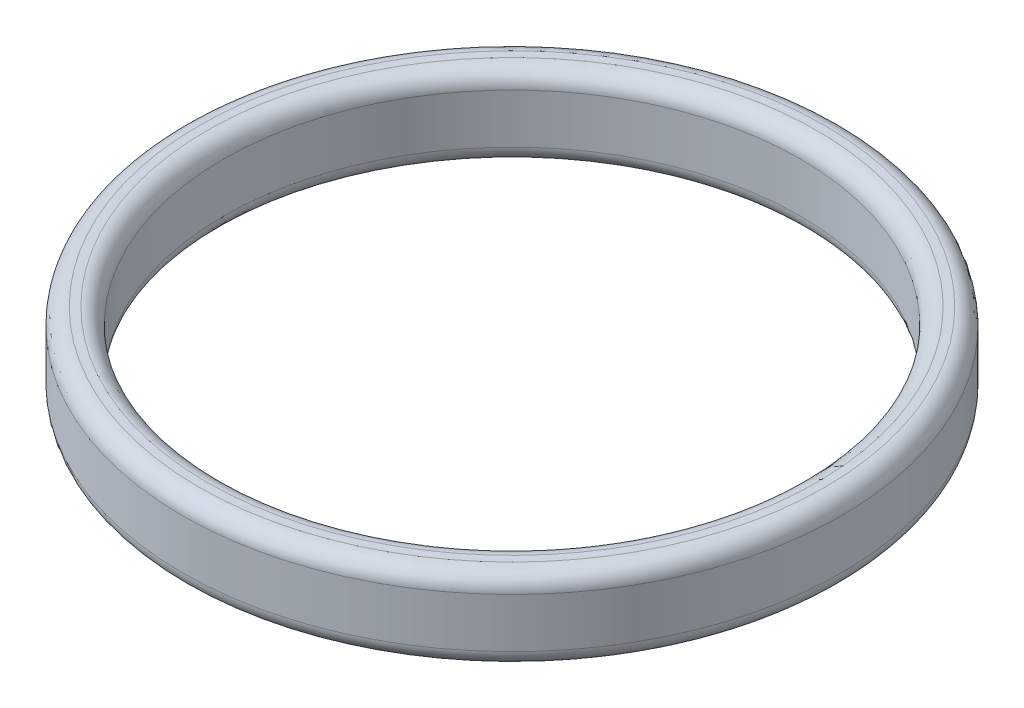
SolidWorks part; units mm, degrees
material "Plain Carbon Steel"
ref_plane "Front Plane" through (0, 0, 0) normal (0, 0, 1) x (1, 0, 0)
ref_plane "Top Plane" through (0, 0, 0) normal (0, 1, 0) x (1, 0, 0)
ref_plane "Right Plane" through (0, 0, 0) normal (1, 0, 0) x (0, 0, -1)
sketch "Sketch1" plane through (0, 0, 0) normal (0, 1, 0) x (1, 0, 0)
  circle A0 centre (0, 0) radius 4
  circle A1 centre (0, 0) radius 3.5
  dimension "D1" = 8
  dimension "D2" = 7
extrude "Boss-Extrude1" add sketch "Sketch1" along normal blind 1
fillet "Fillet1" radius 0.2 4 edges at (0, 1, 3.5) (0, 1, 4) (0, 0, 3.5) (0, 0, 4)
